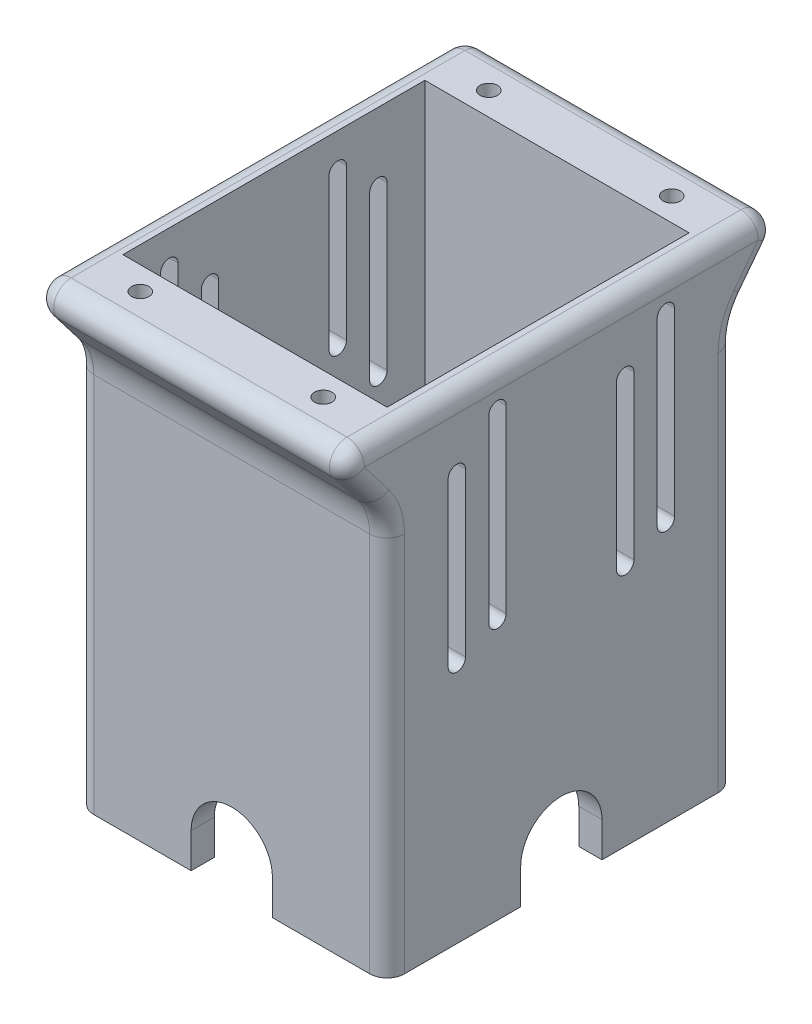
SolidWorks part; units mm, degrees
ref_plane "Front Plane" through (0, 0, 0) normal (0, 0, 1) x (1, 0, 0)
ref_plane "Top Plane" through (0, 0, 0) normal (0, 1, 0) x (1, 0, 0)
ref_plane "Right Plane" through (0, 0, 0) normal (1, 0, 0) x (0, 0, -1)
sketch "Sketch1" plane through (0, 0, 0) normal (0, 1, 0) x (1, 0, 0)
  line L1 (-26.75, 30) -> (26.75, 30)
  line L2 (-26.75, 30) -> (-26.75, -30)
  line L3 (-26.75, -30) -> (26.75, -30)
  line L4 (26.75, 30) -> (26.75, -30)
  line L5 (-26.75, 30) -> (26.75, -30) construction
  line L6 (-26.75, -30) -> (26.75, 30) construction
  line L7 (-22.75, 26) -> (22.75, 26)
  line L8 (-22.75, 26) -> (-22.75, -26)
  line L9 (-22.75, -26) -> (22.75, -26)
  line L10 (22.75, 26) -> (22.75, -26)
  line L11 (-22.75, 26) -> (22.75, -26) construction
  line L12 (-22.75, -26) -> (22.75, 26) construction
  point P0 (0, 0)
  point P6 (0, 0)
  dimension "D1" = 45.5
  dimension "D2" = 4
  dimension "D3" = 4
extrude "Boss-Extrude1" add sketch "Sketch1" along normal blind 82
sketch "Sketch3" plane through (-26.75, 0, 0) normal (-1, 0, 0) x (0, 0, 1)
  line L1 (18, 76) -> (18, 50) construction
  line L2 (19.5, 76) -> (19.5, 50)
  line L3 (16.5, 76) -> (16.5, 50)
  line L4 (-30, 82) -> (30, 82) construction
  line L5 (-30, 0) -> (30, 0) construction
  line L6 (11, 70) -> (11, 42) construction
  line L7 (12.5, 70) -> (12.5, 42)
  line L8 (9.5, 70) -> (9.5, 42)
  arc A2 (19.5, 76) -> (16.5, 76) centre (18, 76) ccw
  arc A3 (16.5, 50) -> (19.5, 50) centre (18, 50) ccw
  arc A4 (12.5, 70) -> (9.5, 70) centre (11, 70) ccw
  arc A5 (9.5, 42) -> (12.5, 42) centre (11, 42) ccw
  point P9 (18, 63)
  point P14 (11, 56)
  point P20 (0, 0)
  point P22 (9.5839, 0)
  dimension "D1" = 6
  dimension "D3" = 8
  dimension "D2" = 50
  dimension "D4" = 3
  dimension "D5" = 7
  dimension "D6" = 12
  dimension "D7" = 3
  dimension "D8" = 42
extrude "Cut-Extrude1" cut sketch "Sketch3" against normal blind 4 and the other way through all
pattern_linear "LPattern1" count 2 spacing 29 along (0, 0, -1) of "Cut-Extrude1"
sketch "Sketch4" plane through (26.75, 0, 0) normal (1, 0, 0) x (0, 0, -1)
  line L0 (-30, 82) -> (30, 82) construction
  line L1 (-11, 76) -> (-11, 45) construction
  line L2 (-9.5, 76) -> (-9.5, 45)
  line L3 (-12.5, 76) -> (-12.5, 45)
  line L4 (-30, 0) -> (30, 0) construction
  line L5 (-18, 70) -> (-18, 42) construction
  line L6 (-16.5, 70) -> (-16.5, 42)
  line L7 (-19.5, 70) -> (-19.5, 42)
  arc A2 (-9.5, 76) -> (-12.5, 76) centre (-11, 76) ccw
  arc A3 (-12.5, 45) -> (-9.5, 45) centre (-11, 45) ccw
  arc A4 (-16.5, 70) -> (-19.5, 70) centre (-18, 70) ccw
  arc A5 (-19.5, 42) -> (-16.5, 42) centre (-18, 42) ccw
  point P8 (-18, 56)
  point P9 (-11, 60.5)
  dimension "D1" = 15
  dimension "D2" = 6
  dimension "D8" = 42
  dimension "D3" = 45
  dimension "D4" = 3
  dimension "D5" = 7
  dimension "D6" = 12
  dimension "D7" = 3
extrude "Cut-Extrude2" cut sketch "Sketch4" against normal blind 4
pattern_linear "LPattern2" count 2 spacing 29 along (0, 0, -1) of "Cut-Extrude2"
sketch "Sketch5" plane through (-26.75, 0, 0) normal (-1, 0, 0) x (0, 0, 1)
  line L0 (30, 82) -> (30, 69)
  line L1 (30, 82) -> (30, 0) construction
  line L2 (30, 69) -> (40, 82)
  line L3 (40, 82) -> (30, 82)
  line L4 (-30, 82) -> (-30, 69)
  line L5 (-30, 82) -> (-30, 0) construction
  line L6 (-30, 69) -> (-40, 82)
  line L7 (-30, 82) -> (-40, 82)
  dimension "D1" = 10
  dimension "D2" = 13
extrude "Boss-Extrude2" add sketch "Sketch5" against normal through all
fillet "Fillet1" radius 10 2 edges at (0, 69, 30) (0, 69, -30)
fillet "Fillet2" radius 3 16 edges at (26.75, 32.7994, -30) (26.75, 68.8188, -30.5326) (26.75, 76.8479, -36.0369) (26.75, 82, 0) (0, 82, -40) (26.75, 32.7994, 30) (26.75, 68.8188, 30.5326) (-26.75, 32.7994, 30) (-26.75, 68.8188, 30.5326) (-26.75, 32.7994, -30) (-26.75, 68.8188, -30.5326) (26.75, 76.8479, 36.0369) (0, 82, 40) (-26.75, 76.8479, 36.0369) (-26.75, 76.8479, -36.0369) (-26.75, 82, 0)
sketch "Sketch6" plane through (0, 82, 0) normal (0, 1, 0) x (1, 0, 0)
  line L0 (-22.75, -26) -> (22.75, -26) construction
  line L2 (-23.75, 33.9074) -> (-23.75, -33.9074) construction
  line L3 (0, -33.9074) -> (0, -26) construction
  line L4 (-23.75, -33.9074) -> (23.75, -33.9074) construction
  circle A0 centre (-15.75, -30) radius 1.5
  circle A1 centre (15.75, -30) radius 1.5
  dimension "D2" = 3
  dimension "D1" = 4
  dimension "D3" = 8
extrude "Cut-Extrude3" cut sketch "Sketch6" against normal blind 9
ref_plane "Plane1" through (0, 0, 0) normal (0, 0, 1) x (1, 0, 0)
mirror "Mirror1" about plane through (0, 0, 0) normal (0, 0, 1) of "Cut-Extrude3"
sketch "Sketch7" plane through (26.75, 0, 0) normal (1, 0, 0) x (0, 0, -1)
  line L0 (7, 0) -> (7, 6)
  line L1 (-27, 0) -> (27, 0) construction
  line L2 (-7, 0) -> (-7, 6)
  line L3 (7, 0) -> (-7, 0)
  arc A0 (-7, 6) -> (7, 6) centre (0, 6) cw
  dimension "D5" = 7
  dimension "D1" = 6
  dimension "D2" = 6
  dimension "D3" = 7
  dimension "D4" = 7
extrude "Cut-Extrude4" cut sketch "Sketch7" against normal through all
sketch "Sketch8" plane through (0, 0, -30) normal (0, 0, -1) x (-1, 0, 0)
  line L0 (7, 0) -> (7, 6)
  line L1 (-23.75, 0) -> (23.75, 0) construction
  line L2 (-7, 0) -> (-7, 6)
  line L3 (7, 0) -> (-7, 0)
  arc A0 (-7, 6) -> (7, 6) centre (0, 6) cw
  dimension "D5" = 7
  dimension "D1" = 6
  dimension "D2" = 6
  dimension "D3" = 7
  dimension "D4" = 7
extrude "Cut-Extrude5" cut sketch "Sketch8" against normal through all
